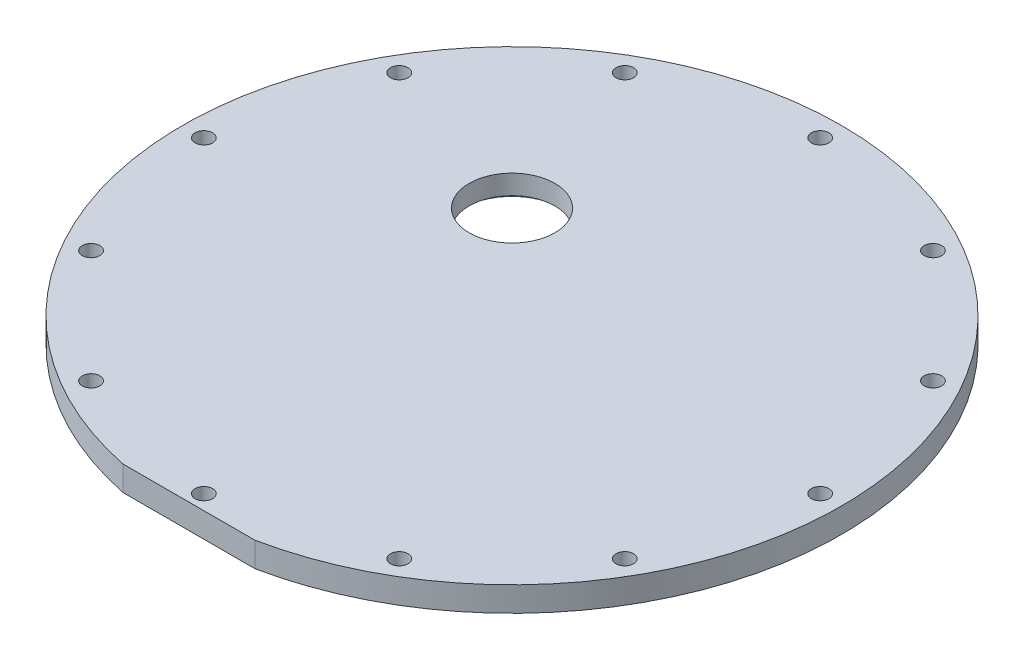
SolidWorks part; units mm, degrees
material "AISI 304"
ref_plane "Front" through (0, 0, 0) normal (0, 0, 1) x (1, 0, 0)
ref_plane "Top" through (0, 0, 0) normal (0, 1, 0) x (1, 0, 0)
ref_plane "Right" through (0, 0, 0) normal (1, 0, 0) x (0, 0, -1)
sketch "Sketch1" plane through (0, 0, 0) normal (0, 0, 1) x (1, 0, 0)
  line L0 (0, 0) -> (0, 9.525)
  line L2 (0, 0) -> (127, 0)
  line L3 (127, 0) -> (127, 9.525)
  line L4 (127, 9.525) -> (0, 9.525)
  dimension "D2" = 127
  dimension "D3" = 9.525
revolve "Revolve1" add sketch "Sketch1" angle 360 about L0
hole_wizard "1/4 Clearance Hole1" positions "Sketch2" profile "Sketch3" hole size "1/4" standard "ANSI Inch" end condition up to next
sketch "Sketch2" plane through (0, 9.525, 0) normal (0, 1, 0) x (1, 0, 0)
  line L0 (0, 0) -> (0, 118.745) construction
  point P0 (0, 118.745)
  point P6 (59.3725, 102.8362)
  point P7 (102.8362, 59.3725)
  point P8 (118.745, 0)
  point P9 (102.8362, -59.3725)
  point P10 (59.3725, -102.8362)
  point P11 (0, -118.745)
  point P12 (-59.3725, -102.8362)
  point P13 (-102.8362, -59.3725)
  point P18 (-118.745, 0)
  point P19 (-102.8362, 59.3725)
  point P20 (-59.3725, 102.8362)
  dimension "D2" = 118.745
  dimension "D1" = 12
sketch "Sketch3" plane through (0, 9.525, -118.745) normal (1, 0, 0) x (0, 0, 1)
  line L0 (0, 0) -> (0, 9.525)
  line L1 (0, 9.525) -> (3.3782, 9.525)
  line L2 (3.3782, 9.525) -> (3.3782, 0)
  line L5 (3.3782, 0) -> (0, 0)
  line L11 (0, -6.35) -> (0, 107.95) construction
  dimension "Thru Hole Dia." = 6.7564
  dimension "Thru Hole Depth" = 9.525
sketch "Sketch4" plane through (0, 9.525, 0) normal (0, 1, 0) x (1, 0, 0)
  line L1 (-25.4, -124.4341) -> (25.4, -124.4341)
  line L2 (-25.4, -124.4341) -> (-25.4, -127)
  line L3 (-25.4, -127) -> (25.4, -127)
  line L4 (25.4, -124.4341) -> (25.4, -127)
  circle A0 centre (0, 0) radius 127 construction
  dimension "D1" = 50.8
extrude "Cut-Extrude1" cut sketch "Sketch4" against normal up to next
sketch "Sketch6" plane through (0, 0, 0) normal (0, -1, 0) x (1, 0, 0)
  line L0 (-35.921, -35.921) -> (0, 0) construction
  line L1 (0, 0) -> (127, 0) construction
  circle A0 centre (-35.921, -35.921) radius 16.51
  circle A1 centre (0, 0) radius 127 construction
  dimension "D1" = 33.02
  dimension "D2" = 135
  dimension "D3" = 50.8
extrude "Cut-Extrude2" cut sketch "Sketch6" against normal up to next
sketch "Sketch7" plane through (0, 0, 0) normal (0, -1, 0) x (1, 0, 0)
  circle A0 centre (-35.921, -35.921) radius 19
  dimension "D1" = 38
extrude "Cut-Extrude3" cut sketch "Sketch7" against normal blind 2
